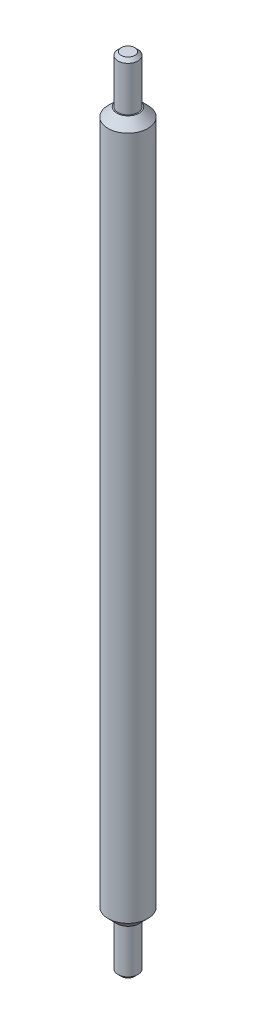
SolidWorks part; units mm, degrees
ref_plane "Ebene vorne" through (0, 0, 0) normal (0, 0, 1) x (1, 0, 0)
ref_plane "Ebene oben" through (0, 0, 0) normal (0, 1, 0) x (1, 0, 0)
ref_plane "Ebene rechts" through (0, 0, 0) normal (1, 0, 0) x (0, 0, -1)
sketch "Skizze1" plane through (0, 0, 0) normal (0, 0, 1) x (1, 0, 0)
  line L0 (0, 0) -> (0, -200) construction
  line L1 (0, 0) -> (2.5, 0)
  line L2 (2.5, 0) -> (2.5, -12)
  line L3 (2.5, -12) -> (5, -12)
  line L4 (5, -12) -> (5, -188)
  line L5 (2.5, -200) -> (0, -200)
  line L6 (0, 0) -> (0, -200)
  line L7 (5, -188) -> (2.5, -188)
  line L8 (2.5, -188) -> (2.5, -200)
  dimension "D1" = 200
  dimension "D2" = 12
  dimension "D3" = 5
  dimension "D4" = 10
  dimension "D5" = 12
revolve "Rotation1" add sketch "Skizze1" angle 360 about L0
chamfer "Fase1" distance 2.2 angle 45 2 edges at (0, -12, 5) (0, -188, 5)
chamfer "Fase2" distance 0.8 angle 45 2 edges at (0, 0, 2.5) (0, -200, 2.5)
